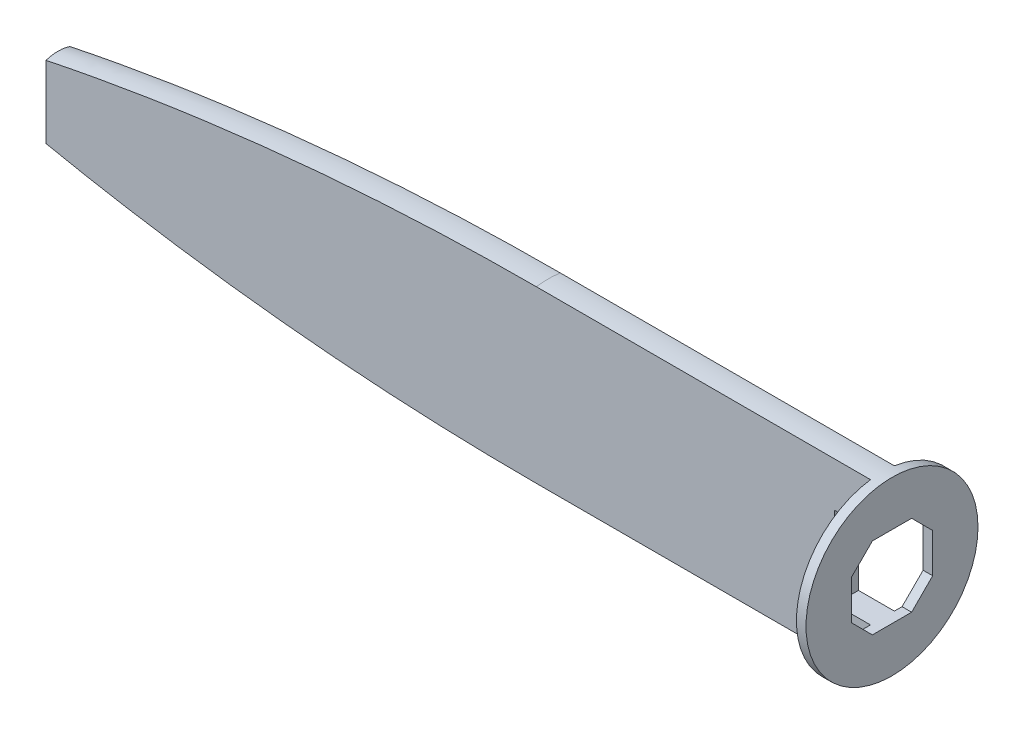
SolidWorks part; units mm, degrees
ref_plane "Front Plane" through (0, 0, 0) normal (0, 0, 1) x (1, 0, 0)
ref_plane "Top Plane" through (0, 0, 0) normal (0, 1, 0) x (1, 0, 0)
ref_plane "Right Plane" through (0, 0, 0) normal (1, 0, 0) x (0, 0, -1)
sketch "Sketch3" plane through (0, 0, 0) normal (0, 0, 1) x (1, 0, 0)
  line L0 (285.7488, 39.71) -> (285.7488, 3.758)
  line L1 (285.7488, 3.758) -> (80.7488, 3.758)
  line L2 (80.7488, 3.758) -> (80.7488, 19.6343)
  spline S0 degree 4 poles (-27.7192, -7.8553) (-27.5014, -7.7876) (-27.0667, -7.6528) (-26.2045, -7.3856) (-24.4548, -6.8463) (-22.0886, -6.1211) (-19.0086, -5.1883) (-15.5879, -4.1634) (-12.0469, -3.1177) (-8.7154, -2.1438) (-5.4871, -1.2149) (-3.2266, -0.5688) (-0.5536, 0.1859) (0.4881, 0.4785) (2.6576, 1.0849) (4.0523, 1.4709) (5.8579, 1.9693) (7.4437, 2.403) (9.5599, 2.9792) (12.0305, 3.6454) (14.9574, 4.4267) (18.2801, 5.3017) (21.6183, 6.1694) (25.7869, 7.2382) (30.7991, 8.5003) (35.8155, 9.7344) (40.8401, 10.9416) (45.8691, 12.1268) (50.9036, 13.2902) (56.7842, 14.6155) (65.1975, 16.4541) (73.6264, 18.2195) (82.0703, 19.9115) (92.2203, 21.8537) (109.1645, 24.9437) (127.868, 27.9778) (146.6331, 30.6047) (163.7338, 32.6585) (174.0045, 33.8015) (184.2848, 34.8552) (194.5761, 35.7972) (204.8769, 36.6272) (213.4665, 37.2443) (220.3412, 37.6932) (227.2189, 38.0972) (233.2386, 38.4115) (238.4005, 38.6528) (242.7017, 38.8352) (246.1452, 38.9699) (249.585, 39.0934) (253.0324, 39.2057) (256.468, 39.3067) (259.9241, 39.3966) (263.347, 39.4752) (266.8257, 39.5425) (270.2119, 39.5987) (273.7565, 39.6436) (276.6051, 39.6731) (279.4395, 39.6913) (281.5976, 39.7039) (285.1517, 39.711) (286.4225, 39.7109) (289.9962, 39.7036) (293.1094, 39.6857) (296.9947, 39.6557) (300.782, 39.6062) (305.3918, 39.5309) (308.4492, 39.4673) (311.2049, 39.4051) (312.9634, 39.3595) (313.8789, 39.3357) (314.3251, 39.3236) knots 0 0 0 0 0 0.00262 0.00524 0.01048 0.02096 0.03144 0.041921 0.052275 0.06263 0.072985 0.078162 0.083339 0.088305 0.093271 0.098237 0.103203 0.108168 0.113134 0.123066 0.132998 0.142929 0.152861 0.162793 0.182656 0.20252 0.212451 0.222383 0.242246 0.26211 0.281973 0.3217 0.341563 0.361427 0.401154 0.520334 0.560061 0.579924 0.599788 0.639515 0.679241 0.699105 0.718968 0.738832 0.758695 0.778558 0.78849 0.798422 0.808354 0.818285 0.828217 0.838149 0.84808 0.858012 0.867944 0.877875 0.887807 0.897739 0.902705 0.907671 0.917602 0.927839 0.932958 0.938076 0.95855 0.968912 0.979275 0.989637 0.994819 1 1 1 1 1 construction
  spline S1 degree 4 poles (80.7488, 19.6343) (82.3471, 19.9504) (85.6364, 20.5939) (92.3118, 21.8704) (109.1645, 24.9437) (127.868, 27.9778) (146.6331, 30.6047) (163.7338, 32.6585) (174.0045, 33.8015) (184.2848, 34.8552) (194.5761, 35.7972) (204.8769, 36.6272) (213.4665, 37.2443) (220.3412, 37.6932) (227.2189, 38.0972) (233.2386, 38.4115) (238.4005, 38.6528) (242.7017, 38.8352) (246.1452, 38.9699) (249.585, 39.0934) (253.0324, 39.2057) (256.468, 39.3067) (259.9241, 39.3966) (263.347, 39.4752) (266.8257, 39.5425) (270.2119, 39.5987) (273.7565, 39.6436) (276.6051, 39.6731) (279.4395, 39.6913) (281.5976, 39.7039) (283.943, 39.7086) (285.0303, 39.71) (285.7488, 39.71) knots 0.322773 0.322773 0.322773 0.322773 0.322773 0.341563 0.361427 0.401154 0.520334 0.560061 0.579924 0.599788 0.639515 0.679241 0.699105 0.718968 0.738832 0.758695 0.778558 0.78849 0.798422 0.808354 0.818285 0.828217 0.838149 0.84808 0.858012 0.867944 0.877875 0.887807 0.897739 0.902705 0.907671 0.917602 0.917602 0.917602 0.917602 0.917602
  dimension "D1" = 35.952
  dimension "D2" = 205
revolve "Revolve1" add sketch "Sketch3" angle 360 about L1
sketch "Sketch6" plane through (285.7488, 0, 0) normal (1, 0, 0) x (0, 0, -1)
  line L5 (-5, 39.67) -> (5, 39.67)
  line L6 (-5, 39.67) -> (-5, -32.154)
  line L15 (-5, -32.154) -> (5, -32.154)
  line L16 (5, 39.67) -> (5, -32.154)
  line L17 (0, -32.154) -> (0, 39.67) construction
  line L18 (-5, 3.758) -> (5, 3.758) construction
  line L19 (5, -32.154) -> (36.0764, -32.154)
  line L20 (5, -32.154) -> (5, 39.67)
  line L21 (5, 39.67) -> (36.0764, 39.67)
  line L22 (36.0764, -32.154) -> (36.0764, 39.67)
  line L23 (-5, 39.67) -> (-36.0314, 39.67)
  line L24 (-5, 39.67) -> (-5, -32.154)
  line L25 (-5, -32.154) -> (-36.0314, -32.154)
  line L26 (-36.0314, 39.67) -> (-36.0314, -32.154)
  point P0 (0, 3.758)
  point P1 (0, 3.758)
  circle M5 centre (0, 3.758) radius 35.952
  dimension "D1" = 5
extrude "Cut-Extrude1" cut sketch "Sketch6" against normal through all contours L6 M5 | L16 M5
sketch "Sketch8" plane through (285.7488, 0, 0) normal (1, 0, 0) x (0, 0, -1)
  line L0 (5, 39.3606) -> (5, -31.8446)
  line L6 (-5, -31.8446) -> (-5, 39.3606)
  circle A2 centre (0, 3.758) radius 35.952
  arc M19 (5, 39.3606) -> (-5, 39.3606) centre (0, 3.758) ccw
  line M20 (-5, 39.3606) -> (-5, -31.8446)
  arc M21 (-5, -31.8446) -> (5, -31.8446) centre (0, 3.758) ccw
  line M22 (5, -31.8446) -> (5, 39.3606)
  dimension "D1" = 71.904
extrude "Boss-Extrude2" add sketch "Sketch8" along normal blind 139.7 contours M22 M19 M20 M21
sketch "Sketch9" plane through (425.4488, 0, 0) normal (1, 0, 0) x (0, 0, -1)
  circle A1 centre (0, 3.758) radius 35.952
  dimension "D1" = 71.904
extrude "Boss-Extrude3" add sketch "Sketch9" along normal blind 4
sketch "Sketch10" plane through (429.4488, 0, 0) normal (1, 0, 0) x (0, 0, -1)
  line L4 (-17, -4.442) -> (-17, 11.958)
  line L5 (-8.2, 20.758) -> (8.2, 20.758)
  line L6 (17, 11.958) -> (17, -4.442)
  line L7 (8.2, -13.242) -> (-8.2, -13.242)
  line L8 (-17, 11.958) -> (-8.2, 20.758)
  line L9 (8.2, 20.758) -> (17, 11.958)
  line L10 (17, -4.442) -> (8.2, -13.242)
  line L11 (-8.2, -13.242) -> (-17, -4.442)
  dimension "D5" = 16.4
  dimension "D7" = 16.4
  dimension "D9" = 16.4
  dimension "D11" = 16.4
extrude "Cut-Extrude2" cut sketch "Sketch10" against normal blind 4
sketch "Sketch11" plane through (425.4488, 0, 0) normal (1, 0, 0) x (0, 0, -1)
  line L1 (-5, 20.758) -> (5, 20.758)
  line L2 (-5, 20.758) -> (-5, -13.242)
  line L3 (-5, -13.242) -> (5, -13.242)
  line L4 (5, 20.758) -> (5, -13.242)
  line L5 (0, -13.242) -> (0, 20.758) construction
  line L6 (-5, 3.758) -> (5, 3.758) construction
  point P0 (0, 3.758)
extrude "Cut-Extrude3" cut sketch "Sketch11" against normal blind 15
